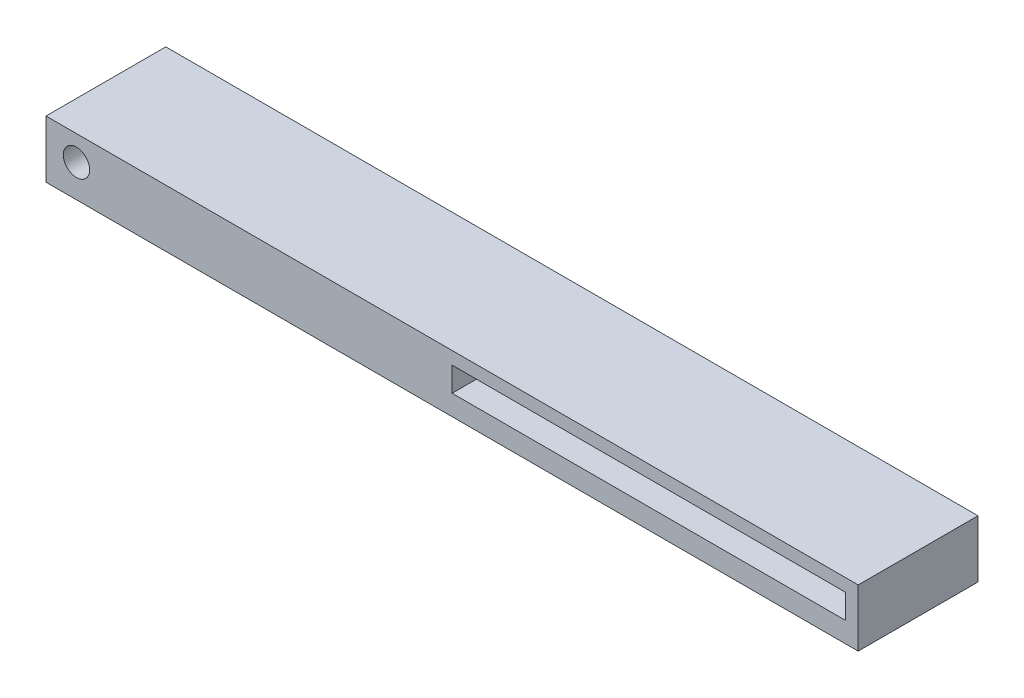
SolidWorks part; units mm, degrees
material "PET"
ref_plane "Front Plane" through (0, 0, 0) normal (0, 0, 1) x (1, 0, 0)
ref_plane "Top Plane" through (0, 0, 0) normal (0, 1, 0) x (1, 0, 0)
ref_plane "Right Plane" through (0, 0, 0) normal (1, 0, 0) x (0, 0, -1)
sketch "Sketch1" plane through (0, 0, 0) normal (0, 1, 0) x (1, 0, 0)
  line L1 (-33.5369, 4.8846) -> (68.0631, 4.8846)
  line L2 (-33.5369, 4.8846) -> (-33.5369, -20.5154)
  line L3 (-33.5369, -20.5154) -> (68.0631, -20.5154)
  line L4 (68.0631, 4.8846) -> (68.0631, -20.5154)
  dimension "D1" = 101.6
  dimension "D2" = 25.4
extrude "Boss-Extrude1" add sketch "Sketch1" along normal blind 2.54
sketch "Sketch2" plane through (0, 0, 0) normal (0, 0, 1) x (1, 0, 0)
  line L0 (17.2631, 2.54) -> (17.2631, 5.588)
  line L1 (-33.5369, 2.54) -> (68.0631, 2.54) construction
  line L2 (17.2631, 5.588) -> (66.4756, 5.588)
  line L3 (66.4756, 5.588) -> (66.4756, 2.54)
  line L4 (-33.5369, 2.54) -> (-33.5369, 0) construction
  line L5 (66.4756, 2.54) -> (68.0631, 2.54)
  line L6 (68.0631, 2.54) -> (68.0631, 7.1755)
  line L7 (68.0631, 7.1755) -> (-33.5369, 7.1755)
  line L8 (-33.5369, 7.1755) -> (-33.5369, 2.54)
  line L9 (-33.5369, 2.54) -> (17.2631, 2.54)
  line L10 (68.0631, 2.54) -> (68.0631, 0) construction
  dimension "D1" = 3.048
  dimension "D2" = 1.5875
  dimension "D3" = 50.8
  dimension "D4" = 1.5875
  dimension "D5" = 0
  dimension "D6" = 0
extrude "Boss-Extrude2" add sketch "Sketch2" along normal blind 19.05 and the other way blind 2.54
sketch "Sketch3" plane through (0, 0, 19.05) normal (0, 0, 1) x (1, 0, 0)
  line L0 (-33.5369, 7.1755) -> (-33.5369, 2.54)
  line L1 (-33.5369, 2.54) -> (17.2631, 2.54)
  line L2 (17.2631, 2.54) -> (17.2631, 5.588)
  line L3 (17.2631, 5.588) -> (66.4756, 5.588)
  line L4 (66.4756, 5.588) -> (66.4756, 2.54)
  line L5 (-33.5369, 2.54) -> (68.0631, 2.54) construction
  line L6 (66.4756, 5.588) -> (66.4756, 2.54) construction
  line L7 (66.4756, 2.54) -> (68.0631, 2.54)
  line L8 (68.0631, 2.54) -> (68.0631, 7.1755)
  line L9 (68.0631, 7.1755) -> (-33.5369, 7.1755)
extrude "Cut-Extrude1" cut sketch "Sketch3" against normal blind 3.81
sketch "Sketch4" plane through (0, 0, -2.54) normal (0, 0, -1) x (-1, 0, 0)
  line L0 (-68.0631, 7.1755) -> (-68.0631, 2.54)
  line L1 (-68.0631, 2.54) -> (-66.4756, 2.54)
  line L2 (-66.4756, 2.54) -> (-66.4756, 5.588)
  line L3 (-66.4756, 5.588) -> (-17.2631, 5.588)
  line L4 (-17.2631, 5.588) -> (-17.2631, 2.54)
  line L5 (-17.2631, 2.54) -> (33.5369, 2.54)
  line L6 (33.5369, 2.54) -> (33.5369, 7.1755)
  line L7 (33.5369, 7.1755) -> (-68.0631, 7.1755)
extrude "Cut-Extrude2" cut sketch "Sketch4" against normal blind 2.794
sketch "Sketch5" plane through (0, 2.54, 0) normal (0, 1, 0) x (1, 0, 0)
  line L1 (-33.5369, 4.8846) -> (68.0631, 4.8846)
  line L2 (-33.5369, 4.8846) -> (-33.5369, -0.254)
  line L3 (-33.5369, -0.254) -> (68.0631, -0.254)
  line L4 (68.0631, 4.8846) -> (68.0631, -0.254)
  line L5 (68.0631, -20.5154) -> (-33.5369, -20.5154)
  line L6 (68.0631, -20.5154) -> (68.0631, -15.24)
  line L7 (68.0631, -15.24) -> (-33.5369, -15.24)
  line L8 (-33.5369, -20.5154) -> (-33.5369, -15.24)
extrude "Cut-Extrude3" cut sketch "Sketch5" against normal blind 3.556
sketch "Sketch6" plane through (0, 0, 15.24) normal (0, 0, 1) x (1, 0, 0)
  line L0 (-33.5369, 7.1755) -> (-33.5369, 0) construction
  line L1 (17.2631, 2.54) -> (17.2631, 5.588) construction
  circle A0 centre (-29.7269, 4.064) radius 1.651
  point P8 (17.2631, 4.064)
  dimension "D1" = 3.302
  dimension "D2" = 3.81
extrude "Cut-Extrude4" cut sketch "Sketch6" against normal through all
